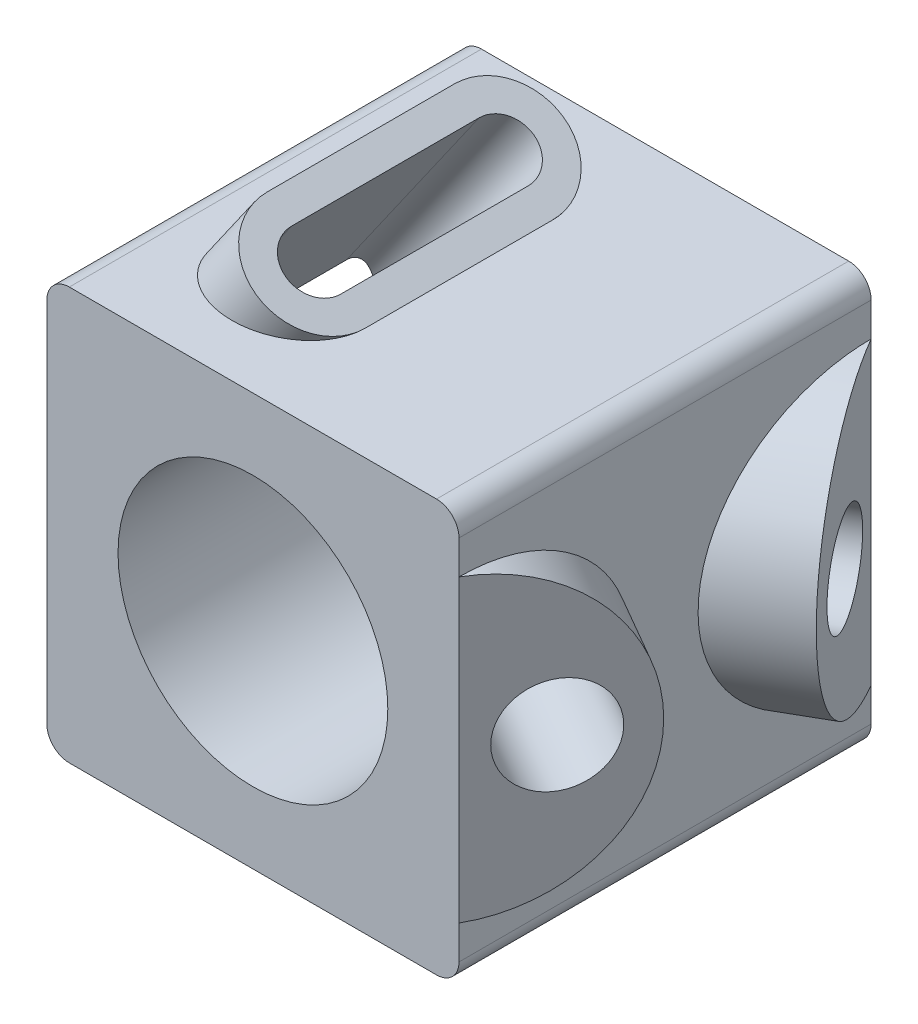
SolidWorks part; units mm, degrees
ref_plane "Front Plane" through (0, 0, 0) normal (0, 0, 1) x (1, 0, 0)
ref_plane "Top Plane" through (0, 0, 0) normal (0, 1, 0) x (1, 0, 0)
ref_plane "Right Plane" through (0, 0, 0) normal (1, 0, 0) x (0, 0, -1)
sketch "Sketch1" plane through (0, 0, 0) normal (0, 0, 1) x (1, 0, 0)
  line L1 (-69.85, -69.85) -> (69.85, -69.85)
  line L2 (-69.85, -69.85) -> (-69.85, 69.85)
  line L3 (-69.85, 69.85) -> (69.85, 69.85)
  line L4 (69.85, -69.85) -> (69.85, 69.85)
  line L5 (-69.85, -69.85) -> (69.85, 69.85) construction
  line L6 (-69.85, 69.85) -> (69.85, -69.85) construction
  point P0 (0, 0)
  dimension "D1" = 139.7
  dimension "D2" = 139.7
extrude "Boss-Extrude1" add sketch "Sketch1" along normal blind 139.7
fillet "Fillet1" radius 7.62 1 edges at (-69.85, 69.85, 69.85)
fillet "Fillet2" radius 7.62 3 edges at (-69.85, -69.85, 69.85) (69.85, -69.85, 69.85) (69.85, 69.85, 69.85)
sketch "Sketch2" plane through (0, 69.85, 0) normal (0, 1, 0) x (1, 0, 0)
  line L0 (0, 0) -> (0, -139.7) construction
  line L1 (62.23, -139.7) -> (-62.23, -139.7) construction
ref_plane "Plane3" through (32.8188, 46.8701, 0) normal (0.5736, 0.8192, 0) x (0, 0, 1)
sketch "Sketch6" plane through (32.8188, 46.8701, 0) normal (0.5736, 0.8192, 0) x (0, 0, 1)
  line L0 (38.0729, -60.3843) -> (101.6271, -60.3843) construction
  line L7 (38.0729, -40.0643) -> (101.6271, -40.0643)
  line L8 (38.0729, -80.7043) -> (101.6271, -80.7043)
  line L9 (0, -40.0643) -> (139.7, -40.0643) construction
  arc A4 (38.0729, -40.0643) -> (38.0729, -80.7043) centre (38.0729, -60.3843) ccw
  arc A5 (101.6271, -80.7043) -> (101.6271, -40.0643) centre (101.6271, -60.3843) ccw
  point P2 (69.85, -60.3843)
  point P9 (69.85, -40.0643)
  dimension "D2" = 20.32
  dimension "D1" = 20.32
extrude "Boss-Extrude3" add sketch "Sketch6" against normal up to next
sketch "Sketch8" plane through (32.8188, 46.8701, 0) normal (0.5736, 0.8192, 0) x (0.8192, -0.5736, 0)
  line L0 (-60.3843, -101.6271) -> (-60.3843, -38.0729) construction
  line L1 (-70.5443, -101.6271) -> (-70.5443, -38.0729)
  line L2 (-50.2243, -101.6271) -> (-50.2243, -38.0729)
  line L3 (-80.7043, -38.0729) -> (-80.7043, -101.6271) construction
  arc A0 (-70.5443, -101.6271) -> (-50.2243, -101.6271) centre (-60.3843, -101.6271) ccw
  arc A1 (-50.2243, -38.0729) -> (-70.5443, -38.0729) centre (-60.3843, -38.0729) ccw
  arc A2 (-40.0643, -38.0729) -> (-80.7043, -38.0729) centre (-60.3843, -38.0729) ccw construction
  arc A5 (-40.0643, -38.0729) -> (-80.7043, -38.0729) centre (-60.3843, -38.0729) ccw construction
  point P2 (-60.3843, -69.85)
  point P10 (-80.7043, -69.85)
  dimension "D1" = 10.16
extrude "Cut-Extrude2" cut sketch "Sketch8" against normal blind 209.804
sketch "Sketch9" plane through (0, 0, 139.7) normal (0, 0, 1) x (1, 0, 0)
  circle A0 centre (0, 0) radius 45.72
  dimension "D1" = 91.44
extrude "Cut-Extrude3" cut sketch "Sketch9" against normal blind 209.804
ref_plane "Plane4" through (52.3875, 0, -30.2459) normal (0.866, 0, -0.5) x (0, 1, 0)
sketch "Sketch10" plane through (52.3875, 0, -30.2459) normal (0.866, 0, -0.5) x (0, 1, 0)
  line L0 (-62.23, 34.925) -> (62.23, 34.925) construction
  line L1 (-50.8, 34.925) -> (50.8, 34.925)
  arc A0 (50.8, 34.925) -> (-50.8, 34.925) centre (0, 34.925) ccw
  dimension "D1" = 101.6
extrude "Boss-Extrude4" add sketch "Sketch10" against normal up to surface up to face at (69.85, 0, 69.85)
sketch "Sketch11" plane through (52.3875, 0, -30.2459) normal (0.866, 0, -0.5) x (-0.5, 0, -0.866)
  line L0 (-34.925, -62.23) -> (-34.925, -50.8) construction
  circle A0 centre (-59.309, 0) radius 16.51
  dimension "D1" = 24.384
  dimension "D2" = 33.02
extrude "Cut-Extrude4" cut sketch "Sketch11" against normal up to surface (32.409 mm away)
ref_plane "Plane5" through (0, 0, 69.85) normal (0, 0, 1) x (1, 0, 0)
mirror "Mirror1" about plane through (0, 0, 69.85) normal (0, 0, 1) of "Cut-Extrude4", "Boss-Extrude4"
